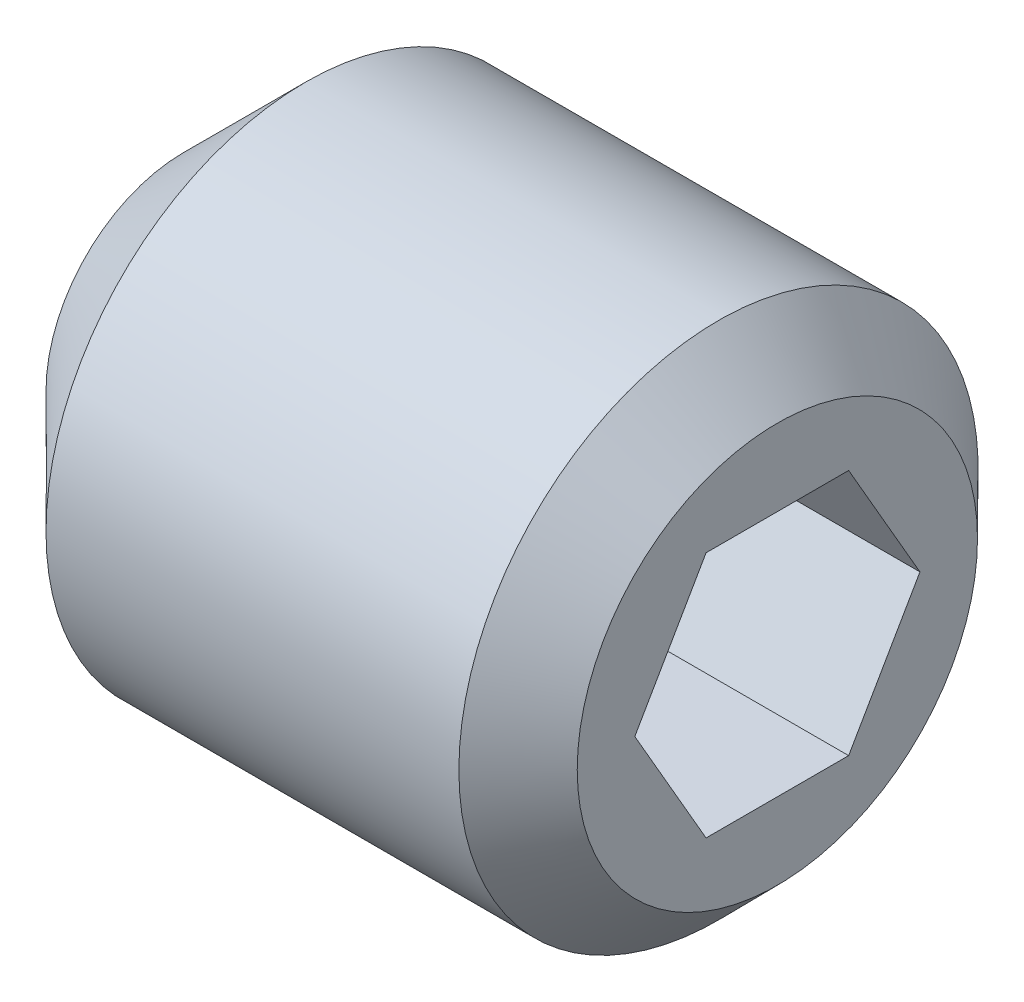
SolidWorks part; units mm, degrees
ref_plane "Front Plane" through (0, 0, 0) normal (0, 0, 1) x (1, 0, 0)
ref_plane "Top Plane" through (0, 0, 0) normal (0, 1, 0) x (1, 0, 0)
ref_plane "Right Plane" through (0, 0, 0) normal (1, 0, 0) x (0, 0, -1)
sketch "Sketch1" plane through (0, 0, 0) normal (1, 0, 0) x (0, 0, -1)
  circle A0 centre (0, 0) radius 2.083
  dimension "D1" = 4.166
extrude "Boss-Extrude1" add sketch "Sketch1" along normal blind 4.762
sketch "Sketch2" plane through (0, 0, 0) normal (0, 0, 1) x (1, 0, 0)
  line L0 (0, 1.105) -> (0.978, 2.083)
  line L1 (0, 2.083) -> (0, -2.083) construction
  line L2 (4.762, 2.083) -> (0, 2.083) construction
  line L3 (0.978, 2.083) -> (0, 2.083)
  line L4 (0, 2.083) -> (0, 1.105)
  dimension "D1" = 0.978
  dimension "D2" = 0.978
ref_axis "Axis1" through (4.762, 0, 0) along (-1, 0, 0)
revolve "Cut-Revolve1" cut sketch "Sketch2" angle 360 about axis through (4.762, 0, 0) along (-1, 0, 0)
sketch "Sketch3" plane through (0, 0, 0) normal (0, 0, 1) x (1, 0, 0)
  line L0 (4.29, 2.083) -> (4.762, 2.083)
  line L1 (4.762, 2.083) -> (0.978, 2.083) construction
  line L2 (4.762, 2.083) -> (4.762, 1.6055)
  line L3 (4.762, -2.083) -> (4.762, 2.083) construction
  line L4 (4.762, 1.6055) -> (4.29, 2.083)
  dimension "D1" = 0.472
  dimension "D2" = 0.4775
revolve "Cut-Revolve2" cut sketch "Sketch3" angle 360 about axis through (4.762, 0, 0) along (-1, 0, 0)
sketch "Sketch11" plane through (0, 0, 0) normal (0, 0, 1) x (1, 0, 0)
  line L0 (0, 0) -> (0, 1.105)
  line L1 (0, 1.105) -> (0, -1.105) construction
  line L4 (0, 0) -> (0.6, 0)
  line L5 (0.6, 0) -> (0, 1.105)
  dimension "D1" = 1.105
  dimension "D2" = 0.6
revolve "Cut-Revolve5" cut sketch "Sketch11" angle 360 about axis through (4.762, 0, 0) along (-1, 0, 0)
sketch "Sketch12" plane through (4.762, 0, 0) normal (1, 0, 0) x (0, 0, -1)
  line L1 (0.5719, 0.9905) -> (-0.5719, 0.9905)
  line L2 (-0.5719, 0.9905) -> (-1.1437, 0)
  line L3 (-1.1437, 0) -> (-0.5719, -0.9905)
  line L4 (-0.5719, -0.9905) -> (0.5719, -0.9905)
  line L5 (0.5719, -0.9905) -> (1.1437, 0)
  line L6 (1.1437, 0) -> (0.5719, 0.9905)
  circle A0 centre (0, 0) radius 0.9905 construction
  dimension "D1" = 1.981
extrude "Cut-Extrude1" cut sketch "Sketch12" against normal blind 2.286
